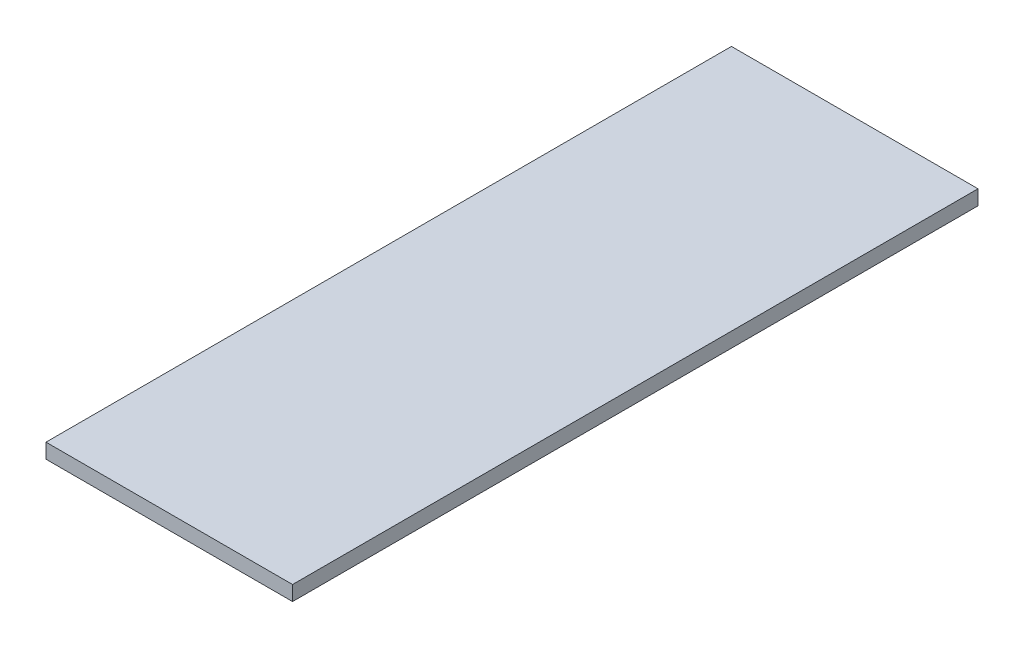
SolidWorks part; units mm, degrees
ref_plane "Front Plane" through (0, 0, 0) normal (0, 0, 1) x (1, 0, 0)
ref_plane "Top Plane" through (0, 0, 0) normal (0, 1, 0) x (1, 0, 0)
ref_plane "Right Plane" through (0, 0, 0) normal (1, 0, 0) x (0, 0, -1)
sketch "Sketch1" plane through (0, 0, 0) normal (0, 1, 0) x (1, 0, 0)
  line L1 (158.75, 441.325) -> (-158.75, 441.325)
  line L2 (158.75, 441.325) -> (158.75, -441.325)
  line L3 (158.75, -441.325) -> (-158.75, -441.325)
  line L4 (-158.75, 441.325) -> (-158.75, -441.325)
  line L5 (158.75, 441.325) -> (-158.75, -441.325) construction
  line L6 (158.75, -441.325) -> (-158.75, 441.325) construction
  point P0 (0, 0)
  dimension "D1" = 317.5
  dimension "D2" = 882.65
extrude "Boss-Extrude1" add sketch "Sketch1" along normal blind 19.05
